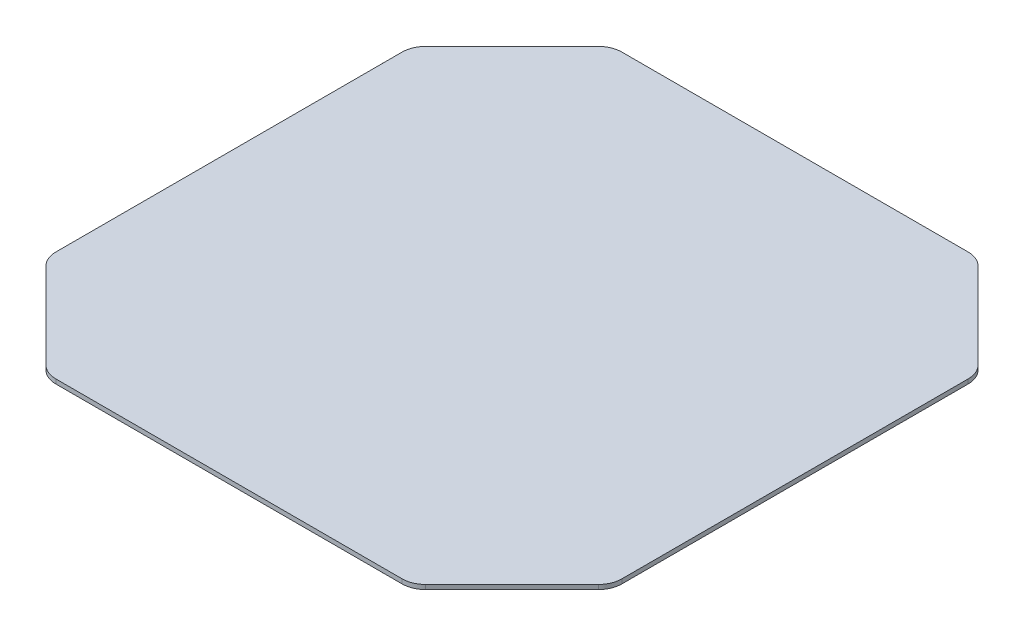
SolidWorks part; units mm, degrees
ref_plane "Front Plane" through (0, 0, 0) normal (0, 0, 1) x (1, 0, 0)
ref_plane "Top Plane" through (0, 0, 0) normal (0, 1, 0) x (1, 0, 0)
ref_plane "Right Plane" through (0, 0, 0) normal (1, 0, 0) x (0, 0, -1)
sketch "Sketch1" plane through (0, 0, 0) normal (0, 1, 0) x (1, 0, 0)
  line L0 (0, 609.6) -> (0, -609.6) construction
  line L1 (-609.6, 609.6) -> (609.6, 609.6)
  line L2 (-609.6, 609.6) -> (-609.6, -609.6)
  line L3 (-609.6, -609.6) -> (609.6, -609.6)
  line L4 (609.6, 609.6) -> (609.6, -609.6)
  dimension "D1" = 1219.2
  dimension "D2" = 1219.2
extrude "Boss-Extrude1" add sketch "Sketch1" along normal blind 9.525
sketch "Sketch2" plane through (0, 9.525, 0) normal (0, 1, 0) x (1, 0, 0)
  line L0 (0, -609.6) -> (0, 609.6) construction
  line L1 (-609.6, -609.6) -> (609.6, -609.6) construction
  line L2 (609.6, 609.6) -> (-609.6, 609.6) construction
  line L3 (-609.6, 0) -> (609.6, 0) construction
  line L4 (-609.6, 609.6) -> (-609.6, -609.6) construction
  line L5 (609.6, -609.6) -> (609.6, 609.6) construction
  circle A0 centre (-609.6, 609.6) radius 152.4
  circle A1 centre (-609.6, -609.6) radius 152.4
  circle A2 centre (609.6, -609.6) radius 152.4
  circle A3 centre (609.6, 609.6) radius 152.4
  point P20 (-609.6, 762)
  point P21 (-762, 609.6)
  dimension "D1" = 304.8
extrude "Cut-Extrude1" cut sketch "Sketch2" against normal up to next
sketch "Sketch3" plane through (0, 9.525, 0) normal (0, 1, 0) x (1, 0, 0)
  line L0 (394.0739, 609.6) -> (609.6, 394.0739)
  line L1 (457.2, 609.6) -> (-457.2, 609.6) construction
  line L2 (609.6, -457.2) -> (609.6, 457.2) construction
  line L3 (394.0739, 609.6) -> (609.6, 609.6) construction
  line L4 (609.6, 609.6) -> (609.6, 394.0739) construction
  circle A0 centre (609.6, 609.6) radius 152.4 construction
extrude "Cut-Extrude2" cut sketch "Sketch3" against normal through all and the other way through all
mirror "Mirror1" about plane through (0, 0, 0) normal (0, 0, 1) of "Cut-Extrude2"
mirror "Mirror2" about plane through (0, 0, 0) normal (1, 0, 0) of "Mirror1", "Cut-Extrude2"
fillet "Fillet1" radius 50.8 8 edges at (394.0739, 4.7625, -609.6) (609.6, 4.7625, -394.0739) (609.6, 4.7625, 394.0739) (394.0739, 4.7625, 609.6) (-394.0739, 4.7625, 609.6) (-609.6, 4.7625, 394.0739) (-394.0739, 4.7625, -609.6) (-609.6, 4.7625, -394.0739)
